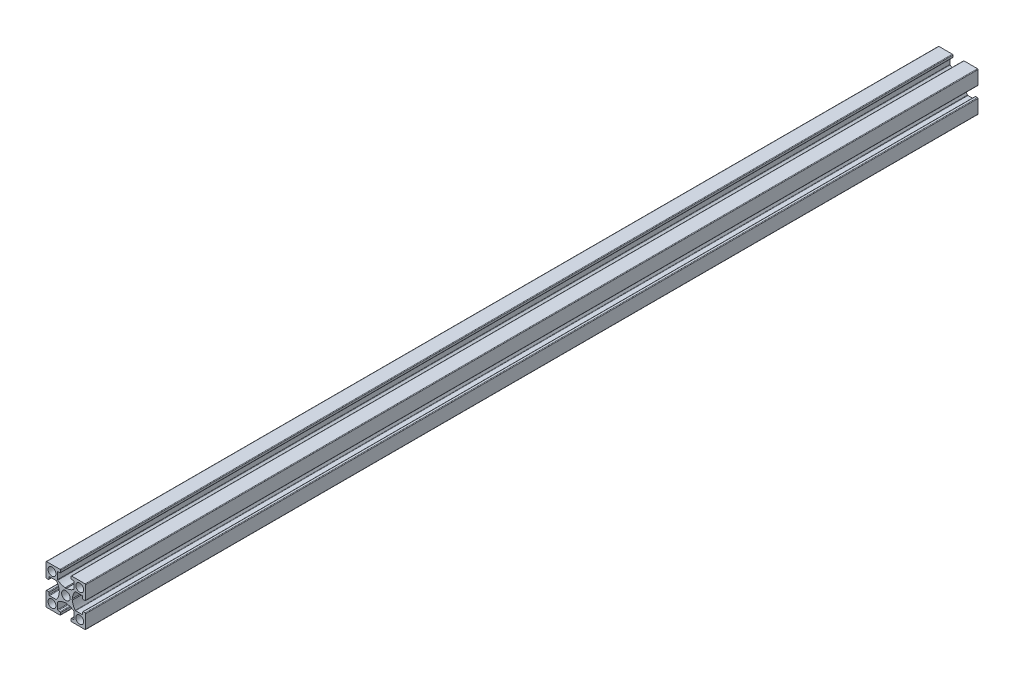
SolidWorks part; units mm, degrees
ref_plane "정면" through (0, 0, 0) normal (0, 0, 1) x (1, 0, 0)
ref_plane "윗면" through (0, 0, 0) normal (0, 1, 0) x (1, 0, 0)
ref_plane "우측면" through (0, 0, 0) normal (1, 0, 0) x (0, 0, -1)
sketch "Model" plane through (0, 0, 0) normal (0, 0, 1) x (1, 0, 0)
  line L0 (2292.4151, 1187.1915) -> (2314.8128, 1187.1915) construction
  line L1 (2307.7639, 1192.1343) -> (2307.7639, 1195.3915)
  line L2 (2307.4639, 1195.6915) -> (2306.5639, 1195.6915)
  line L3 (2306.2639, 1195.9915) -> (2306.2639, 1196.8915)
  line L4 (2306.5639, 1197.1915) -> (2313.3139, 1197.1915)
  line L5 (2313.6139, 1196.8915) -> (2313.6139, 1190.1415)
  line L6 (2313.3139, 1189.8415) -> (2312.4139, 1189.8415)
  line L7 (2312.1139, 1190.1415) -> (2312.1139, 1191.0415)
  line L8 (2311.8139, 1191.3415) -> (2308.5567, 1191.3415)
  line L9 (2306.9212, 1187.4988) -> (2306.6139, 1187.1915)
  line L10 (2306.6139, 1187.1915) -> (2306.9212, 1186.8843)
  line L11 (2308.5567, 1183.0415) -> (2311.8139, 1183.0415)
  line L12 (2312.1139, 1183.3415) -> (2312.1139, 1184.2415)
  line L13 (2312.4139, 1184.5415) -> (2313.3139, 1184.5415)
  line L14 (2313.6139, 1184.2415) -> (2313.6139, 1177.4915)
  line L15 (2313.3139, 1177.1915) -> (2306.5639, 1177.1915)
  line L16 (2306.2639, 1177.4915) -> (2306.2639, 1178.3915)
  line L17 (2306.5639, 1178.6915) -> (2307.4639, 1178.6915)
  line L18 (2307.7639, 1178.9915) -> (2307.7639, 1182.2488)
  line L19 (2303.9212, 1183.8843) -> (2303.6139, 1184.1915)
  line L20 (2303.6139, 1184.1915) -> (2303.3066, 1183.8843)
  line L21 (2299.4639, 1182.2488) -> (2299.4639, 1178.9915)
  line L22 (2299.7639, 1178.6915) -> (2300.6639, 1178.6915)
  line L23 (2300.9639, 1178.3915) -> (2300.9639, 1177.4915)
  line L24 (2300.6639, 1177.1915) -> (2293.9139, 1177.1915)
  line L25 (2293.6139, 1177.4915) -> (2293.6139, 1184.2415)
  line L26 (2293.9139, 1184.5415) -> (2294.8139, 1184.5415)
  line L27 (2295.1139, 1184.2415) -> (2295.1139, 1183.3415)
  line L28 (2295.4139, 1183.0415) -> (2298.6712, 1183.0415)
  line L29 (2300.3066, 1186.8843) -> (2300.6139, 1187.1915)
  line L30 (2300.6139, 1187.1915) -> (2300.3066, 1187.4988)
  line L31 (2298.6712, 1191.3415) -> (2295.4139, 1191.3415)
  line L32 (2295.1139, 1191.0415) -> (2295.1139, 1190.1415)
  line L33 (2294.8139, 1189.8415) -> (2293.9139, 1189.8415)
  line L34 (2293.6139, 1190.1415) -> (2293.6139, 1196.8915)
  line L35 (2293.9139, 1197.1915) -> (2300.6639, 1197.1915)
  line L36 (2300.9639, 1196.8915) -> (2300.9639, 1195.9915)
  line L37 (2300.6639, 1195.6915) -> (2299.7639, 1195.6915)
  line L38 (2299.4639, 1195.3915) -> (2299.4639, 1192.1343)
  line L39 (2303.3066, 1190.4988) -> (2303.6139, 1190.1915)
  line L40 (2303.6139, 1190.1915) -> (2303.9212, 1190.4988)
  line L41 (2294.1139, 1194.1915) -> (2299.1139, 1194.1915) construction
  line L42 (2296.6139, 1196.6915) -> (2296.6139, 1191.6915) construction
  line L43 (2294.1139, 1180.1915) -> (2299.1139, 1180.1915) construction
  line L44 (2296.6139, 1177.6915) -> (2296.6139, 1182.6915) construction
  line L45 (2303.6139, 1198.3904) -> (2303.6139, 1175.9927) construction
  line L46 (2313.1139, 1194.1915) -> (2308.1139, 1194.1915) construction
  line L47 (2310.6139, 1196.6915) -> (2310.6139, 1191.6915) construction
  line L48 (2310.6139, 1177.6915) -> (2310.6139, 1182.6915) construction
  line L49 (2313.1139, 1180.1915) -> (2308.1139, 1180.1915) construction
  circle A0 centre (2303.6139, 1187.1915) radius 2.15
  circle A1 centre (2296.6139, 1194.1915) radius 2
  circle A2 centre (2296.6139, 1180.1915) radius 2
  circle A3 centre (2310.6139, 1194.1915) radius 2
  circle A4 centre (2310.6139, 1180.1915) radius 2
  arc A5 (2307.7639, 1195.3915) -> (2307.4639, 1195.6915) centre (2307.4639, 1195.3915) ccw
  arc A6 (2306.2639, 1195.9915) -> (2306.5639, 1195.6915) centre (2306.5639, 1195.9915) ccw
  arc A7 (2306.5639, 1197.1915) -> (2306.2639, 1196.8915) centre (2306.5639, 1196.8915) ccw
  arc A8 (2313.6139, 1196.8915) -> (2313.3139, 1197.1915) centre (2313.3139, 1196.8915) ccw
  arc A9 (2313.3139, 1189.8415) -> (2313.6139, 1190.1415) centre (2313.3139, 1190.1415) ccw
  arc A10 (2312.1139, 1190.1415) -> (2312.4139, 1189.8415) centre (2312.4139, 1190.1415) ccw
  arc A11 (2312.1139, 1191.0415) -> (2311.8139, 1191.3415) centre (2311.8139, 1191.0415) ccw
  arc A12 (2308.5567, 1191.3415) -> (2308.3217, 1191.2281) centre (2308.5567, 1191.0415) ccw
  arc A13 (2308.3217, 1191.2281) -> (2306.9212, 1187.4988) centre (2313.4048, 1187.1915) ccw
  arc A14 (2306.9212, 1186.8843) -> (2308.3217, 1183.155) centre (2313.4048, 1187.1915) ccw
  arc A15 (2308.3217, 1183.155) -> (2308.5567, 1183.0415) centre (2308.5567, 1183.3415) ccw
  arc A16 (2311.8139, 1183.0415) -> (2312.1139, 1183.3415) centre (2311.8139, 1183.3415) ccw
  arc A17 (2312.4139, 1184.5415) -> (2312.1139, 1184.2415) centre (2312.4139, 1184.2415) ccw
  arc A18 (2313.6139, 1184.2415) -> (2313.3139, 1184.5415) centre (2313.3139, 1184.2415) ccw
  arc A19 (2313.3139, 1177.1915) -> (2313.6139, 1177.4915) centre (2313.3139, 1177.4915) ccw
  arc A20 (2306.2639, 1177.4915) -> (2306.5639, 1177.1915) centre (2306.5639, 1177.4915) ccw
  arc A21 (2306.5639, 1178.6915) -> (2306.2639, 1178.3915) centre (2306.5639, 1178.3915) ccw
  arc A22 (2307.4639, 1178.6915) -> (2307.7639, 1178.9915) centre (2307.4639, 1178.9915) ccw
  arc A23 (2307.7639, 1182.2488) -> (2307.6505, 1182.4837) centre (2307.4639, 1182.2488) ccw
  arc A24 (2307.6505, 1182.4837) -> (2303.9212, 1183.8843) centre (2303.6139, 1177.4007) ccw
  arc A25 (2303.3066, 1183.8843) -> (2299.5774, 1182.4837) centre (2303.6139, 1177.4007) ccw
  arc A26 (2299.5774, 1182.4837) -> (2299.4639, 1182.2488) centre (2299.7639, 1182.2488) ccw
  arc A27 (2299.4639, 1178.9915) -> (2299.7639, 1178.6915) centre (2299.7639, 1178.9915) ccw
  arc A28 (2300.9639, 1178.3915) -> (2300.6639, 1178.6915) centre (2300.6639, 1178.3915) ccw
  arc A29 (2300.6639, 1177.1915) -> (2300.9639, 1177.4915) centre (2300.6639, 1177.4915) ccw
  arc A30 (2293.6139, 1177.4915) -> (2293.9139, 1177.1915) centre (2293.9139, 1177.4915) ccw
  arc A31 (2293.9139, 1184.5415) -> (2293.6139, 1184.2415) centre (2293.9139, 1184.2415) ccw
  arc A32 (2295.1139, 1184.2415) -> (2294.8139, 1184.5415) centre (2294.8139, 1184.2415) ccw
  arc A33 (2295.1139, 1183.3415) -> (2295.4139, 1183.0415) centre (2295.4139, 1183.3415) ccw
  arc A34 (2298.6712, 1183.0415) -> (2298.9061, 1183.155) centre (2298.6712, 1183.3415) ccw
  arc A35 (2298.9061, 1183.155) -> (2300.3066, 1186.8843) centre (2293.8231, 1187.1915) ccw
  arc A36 (2300.3066, 1187.4988) -> (2298.9061, 1191.2281) centre (2293.8231, 1187.1915) ccw
  arc A37 (2298.9061, 1191.2281) -> (2298.6712, 1191.3415) centre (2298.6712, 1191.0415) ccw
  arc A38 (2295.4139, 1191.3415) -> (2295.1139, 1191.0415) centre (2295.4139, 1191.0415) ccw
  arc A39 (2294.8139, 1189.8415) -> (2295.1139, 1190.1415) centre (2294.8139, 1190.1415) ccw
  arc A40 (2293.6139, 1190.1415) -> (2293.9139, 1189.8415) centre (2293.9139, 1190.1415) ccw
  arc A41 (2293.9139, 1197.1915) -> (2293.6139, 1196.8915) centre (2293.9139, 1196.8915) ccw
  arc A42 (2300.9639, 1196.8915) -> (2300.6639, 1197.1915) centre (2300.6639, 1196.8915) ccw
  arc A43 (2300.6639, 1195.6915) -> (2300.9639, 1195.9915) centre (2300.6639, 1195.9915) ccw
  arc A44 (2299.7639, 1195.6915) -> (2299.4639, 1195.3915) centre (2299.7639, 1195.3915) ccw
  arc A45 (2299.4639, 1192.1343) -> (2299.5774, 1191.8994) centre (2299.7639, 1192.1343) ccw
  arc A46 (2299.5774, 1191.8994) -> (2303.3066, 1190.4988) centre (2303.6139, 1196.9824) ccw
  arc A47 (2303.9212, 1190.4988) -> (2307.6505, 1191.8994) centre (2303.6139, 1196.9824) ccw
  arc A48 (2307.6505, 1191.8994) -> (2307.7639, 1192.1343) centre (2307.4639, 1192.1343) ccw
extrude "보스-돌출1" add sketch "Model" along normal blind 450
